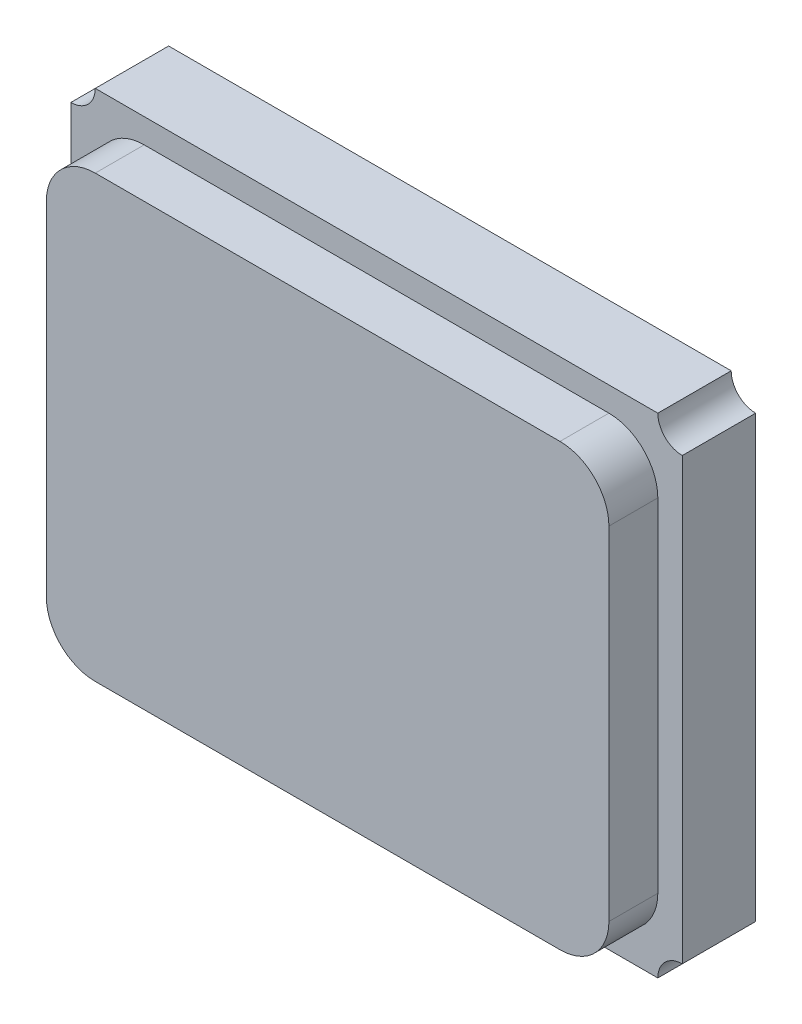
SolidWorks part; units mm, degrees
ref_plane "Plan de face" through (0, 0, 0) normal (0, 0, 1) x (1, 0, 0)
ref_plane "Plan de dessus" through (0, 0, 0) normal (0, 1, 0) x (1, 0, 0)
ref_plane "Plan de droite" through (0, 0, 0) normal (1, 0, 0) x (0, 0, -1)
sketch "Esquisse1" plane through (0, 0, 0) normal (0, 0, 1) x (1, 0, 0)
  line L0 (1.4264, 0) -> (-1.5937, 0) construction
  line L1 (0, 1.3335) -> (0, -1.3091) construction
  line L2 (-1.25, -0.9) -> (-1.25, 0.9)
  line L3 (1.15, 1) -> (-1.15, 1)
  line L8 (1.15, -1) -> (-1.15, -1)
  line L13 (1.25, -0.9) -> (1.25, 0.9)
  arc A0 (-1.25, 0.9) -> (-1.15, 1) centre (-1.25, 1) ccw
  arc A1 (-1.25, -0.9) -> (-1.15, -1) centre (-1.25, -1) cw
  arc A2 (1.25, -0.9) -> (1.15, -1) centre (1.25, -1) ccw
  arc A3 (1.25, 0.9) -> (1.15, 1) centre (1.25, 1) cw
  point P24 (0, -1)
  point P28 (0, 1)
  dimension "D1" = 0.1
  dimension "D5" = 2.5
  dimension "D6" = 2
extrude "semelle" add sketch "Esquisse1" along normal blind 0.3
sketch "Esquisse2" plane through (0, 0, 0.3) normal (0, 0, 1) x (1, 0, 0)
  line L0 (-1.5075, 0) -> (1.473, 0) construction
  line L1 (0, 1) -> (0, -1) construction
  line L2 (-0.95, 0.9) -> (0.95, 0.9)
  line L3 (1.15, 0.7) -> (1.15, -0.7)
  line L4 (-0.95, -0.9) -> (0.95, -0.9)
  line L5 (-1.15, 0.7) -> (-1.15, -0.7)
  line L8 (1.15, 1) -> (-1.15, 1) construction
  line L9 (-1.15, -1) -> (1.15, -1) construction
  arc A0 (0.95, 0.9) -> (1.15, 0.7) centre (0.95, 0.7) cw
  arc A1 (0.95, -0.9) -> (1.15, -0.7) centre (0.95, -0.7) ccw
  arc A2 (-0.95, -0.9) -> (-1.15, -0.7) centre (-0.95, -0.7) cw
  arc A3 (-0.95, 0.9) -> (-1.15, 0.7) centre (-0.95, 0.7) ccw
  point P8 (0, 0.9)
  point P13 (1.15, 0)
  point P20 (0, -0.9)
  dimension "D1" = 0.2
  dimension "D2" = 2.3
  dimension "D3" = 1.8
extrude "couvercle" add sketch "Esquisse2" along normal blind 0.2
